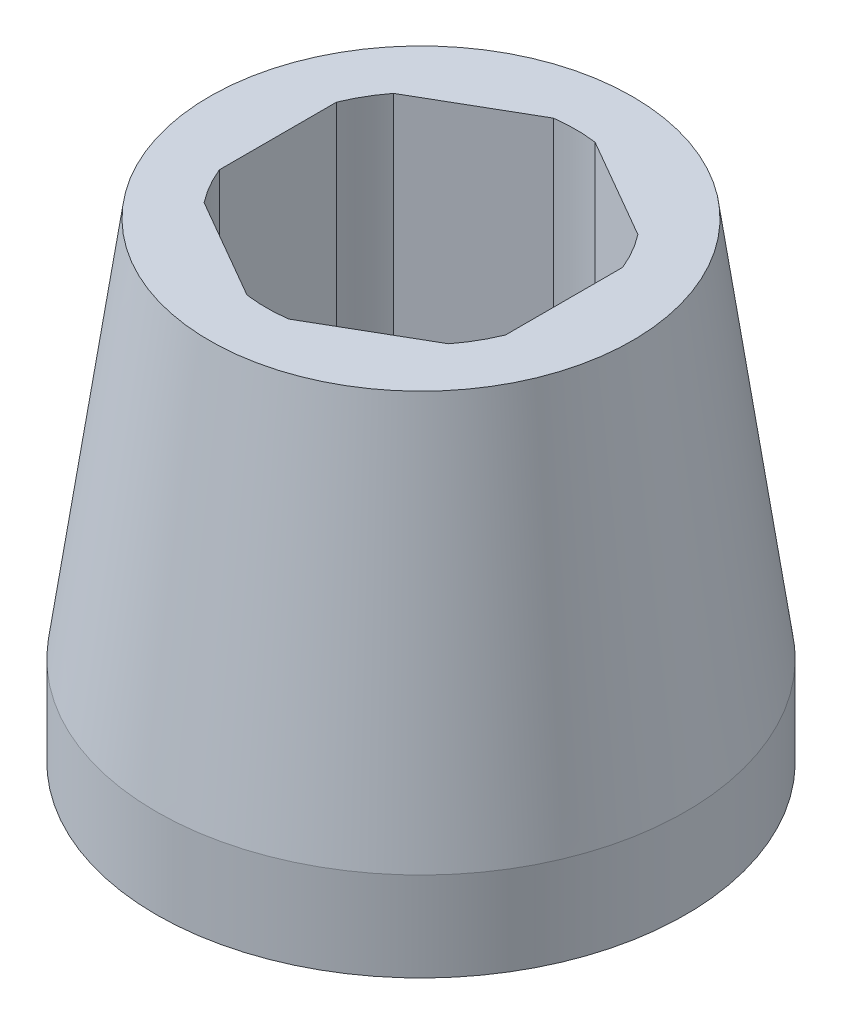
SolidWorks part; units mm, degrees
ref_plane "Front Plane" through (0, 0, 0) normal (0, 0, 1) x (1, 0, 0)
ref_plane "Top Plane" through (0, 0, 0) normal (0, 1, 0) x (1, 0, 0)
ref_plane "Right Plane" through (0, 0, 0) normal (1, 0, 0) x (0, 0, -1)
sketch "Sketch1" plane through (0, 0, 0) normal (0, 0, 1) x (1, 0, 0)
  line L0 (6.8, 0) -> (6.8, 4.953)
  line L1 (6.8, 4.953) -> (5.2, 4.953)
  line L2 (5.2, 4.953) -> (5.2, 15.829)
  line L3 (5.2, 15.829) -> (7.112, 15.829)
  line L7 (8.9, 0) -> (6.8, 0)
  line L8 (7.112, 15.829) -> (8.9, 3)
  line L9 (8.9, 3) -> (8.9, 0)
  line L10 (0, 0) -> (0, 16.4092) construction
  point P6 (0, 0)
  dimension "D1" = 6.8
  dimension "D3" = 4.953
  dimension "D4" = 8.9
  dimension "D5" = 15.829
  dimension "D7" = 3
  dimension "D8" = 7.112
  dimension "D9" = 5.2
revolve "Revolve1" add sketch "Sketch1" angle 360 about L10
sketch "Sketch4" plane through (0, 4.953, 0) normal (0, -1, 0) x (1, 0, 0)
  line L1 (4.8125, 2.7785) -> (0, 5.557)
  line L2 (0, 5.557) -> (-4.8125, 2.7785)
  line L3 (-4.8125, 2.7785) -> (-4.8125, -2.7785)
  line L4 (-4.8125, -2.7785) -> (0, -5.557)
  line L5 (0, -5.557) -> (4.8125, -2.7785)
  line L6 (4.8125, -2.7785) -> (4.8125, 2.7785)
  circle A0 centre (0, 0) radius 4.8125 construction
  circle A1 centre (0, 0) radius 5.2 construction
  circle A2 centre (0, 0) radius 5.2
  circle M9 centre (0, 0) radius 5.2
  dimension "D1" = 9.625
extrude "Boss-Extrude1" add sketch "Sketch4" against normal up to surface (10.876 mm away) contours L2 M9 | L3 M9 | L4 M9 | L5 M9 | L6 M9 | L1 M9 | A2
chamfer "Chamfer1" distance 0.75 angle 45 1 edges at (0, 0, -6.8)
